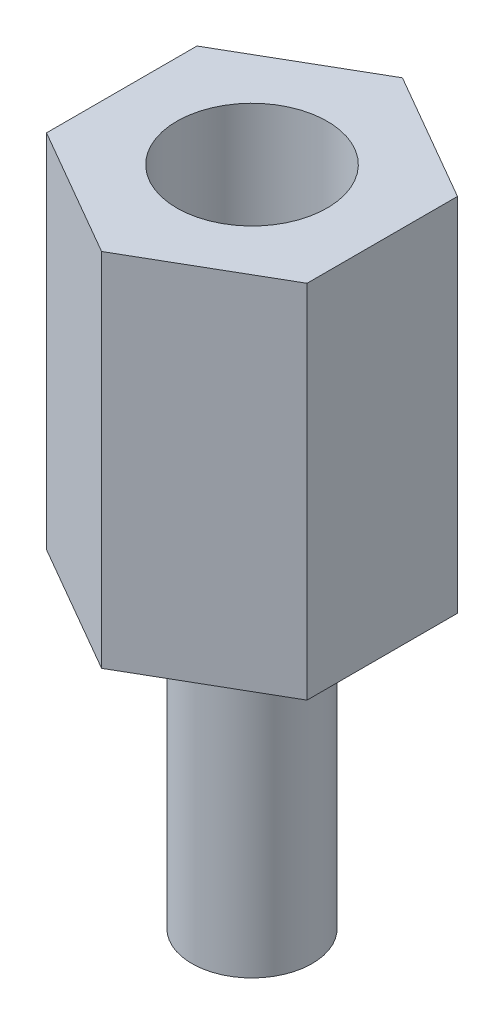
SolidWorks part; units mm, degrees
ref_plane "Front Plane" through (0, 0, 0) normal (0, 0, 1) x (1, 0, 0)
ref_plane "Top Plane" through (0, 0, 0) normal (0, 1, 0) x (1, 0, 0)
ref_plane "Right Plane" through (0, 0, 0) normal (1, 0, 0) x (0, 0, -1)
sketch "Sketch1" plane through (0, 0, 0) normal (0, 1, 0) x (1, 0, 0)
  line L1 (0, 2.5) -> (-2.1651, 1.25)
  line L2 (-2.1651, 1.25) -> (-2.1651, -1.25)
  line L3 (-2.1651, -1.25) -> (0, -2.5)
  line L4 (0, -2.5) -> (2.1651, -1.25)
  line L5 (2.1651, -1.25) -> (2.1651, 1.25)
  line L6 (2.1651, 1.25) -> (0, 2.5)
  circle A0 centre (0, 0) radius 2.5 construction
  circle A1 centre (0, 0) radius 1.25
  dimension "D1" = 5
  dimension "D2" = 2.5
extrude "Body" add sketch "Sketch1" along normal blind 5
sketch "Sketch2" plane through (0, 0, 0) normal (0, -1, 0) x (1, 0, 0)
  line L6 (0, -2.5) -> (2.1651, -1.25)
  line L7 (2.1651, -1.25) -> (2.1651, 1.25)
  line L8 (2.1651, 1.25) -> (0, 2.5)
  line L9 (0, 2.5) -> (-2.1651, 1.25)
  line L10 (-2.1651, 1.25) -> (-2.1651, -1.25)
  line L11 (-2.1651, -1.25) -> (0, -2.5)
  line L12 (0, -2.5) -> (2.1651, -1.25)
  line L13 (2.1651, -1.25) -> (2.1651, 1.25)
  line L14 (2.1651, 1.25) -> (0, 2.5)
  line L15 (0, 2.5) -> (-2.1651, 1.25)
  line L16 (-2.1651, 1.25) -> (-2.1651, -1.25)
  line L17 (-2.1651, -1.25) -> (0, -2.5)
  dimension "D1" = 0
extrude "End" add sketch "Sketch2" along normal blind 1
sketch "Sketch3" plane through (0, -1, 0) normal (0, -1, 0) x (1, 0, 0)
  circle A0 centre (0, 0) radius 1
  dimension "D1" = 2
extrude "Screw" add sketch "Sketch3" along normal blind 5
